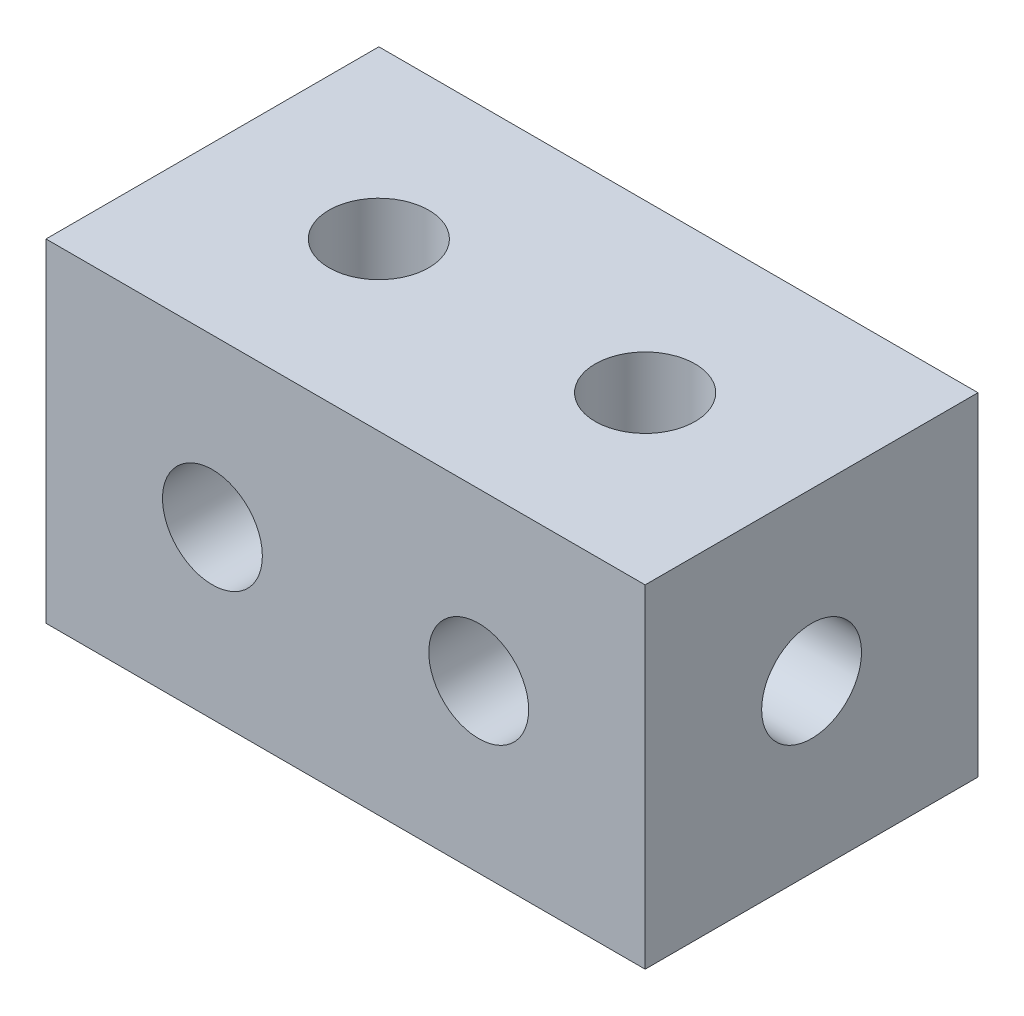
SolidWorks part; units mm, degrees
ref_plane "前视基准面" through (0, 0, 0) normal (0, 0, 1) x (1, 0, 0)
ref_plane "上视基准面" through (0, 0, 0) normal (0, 1, 0) x (1, 0, 0)
ref_plane "右视基准面" through (0, 0, 0) normal (1, 0, 0) x (0, 0, -1)
sketch "草图1" plane through (0, 0, 0) normal (0, 1, 0) x (1, 0, 0)
  line L1 (-9, 5) -> (9, 5)
  line L2 (-9, 5) -> (-9, -5)
  line L3 (-9, -5) -> (9, -5)
  line L4 (9, 5) -> (9, -5)
  circle A0 centre (-4, 0) radius 1.5
  circle A1 centre (4, 0) radius 1.5
  point P0 (0, 0)
  dimension "D4" = 5
  dimension "D5" = 5
  dimension "D1" = 10
  dimension "D2" = 18
  dimension "D3" = 5
  dimension "D6" = 5
extrude "凸台-拉伸1" add sketch "草图1" along normal blind 10
sketch "草图2" plane through (0, 0, 5) normal (0, 0, 1) x (1, 0, 0)
  line L0 (-9, 10) -> (-9, 0) construction
  line L1 (-9, 0) -> (9, 0) construction
  line L2 (9, 10) -> (9, 0) construction
  circle A0 centre (-4, 5) radius 1.5
  circle A1 centre (4, 5) radius 1.5
  dimension "D1" = 5
  dimension "D2" = 5
  dimension "D3" = 5
  dimension "D4" = 5
extrude "切除-拉伸1" cut sketch "草图2" against normal blind 10
sketch "草图4" plane through (-9, 0, 0) normal (-1, 0, 0) x (0, 0, 1)
  line L0 (-5, 10) -> (-5, 0) construction
  line L1 (-5, 0) -> (5, 0) construction
  circle A0 centre (0, 5) radius 1.5
  dimension "D1" = 5
  dimension "D2" = 5
extrude "切除-拉伸2" cut sketch "草图4" against normal blind 25
